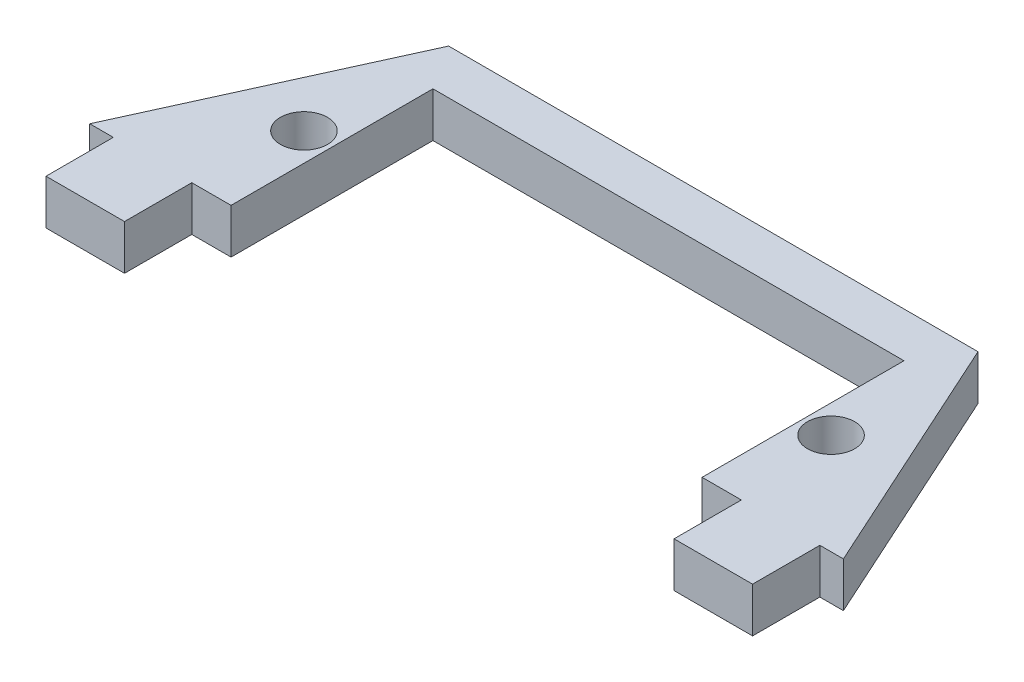
SolidWorks part; units mm, degrees
ref_plane "Front" through (0, 0, 0) normal (0, 0, 1) x (1, 0, 0)
ref_plane "Top" through (0, 0, 0) normal (0, 1, 0) x (1, 0, 0)
ref_plane "Right" through (0, 0, 0) normal (1, 0, 0) x (0, 0, -1)
sketch "Croquis1" plane through (0, 0, 0) normal (0, 1, 0) x (1, 0, 0)
  line L0 (-319.2972, 0) -> (15645.5623, 0) construction
  line L1 (0, -319.2972) -> (0, 15645.5623) construction
  line L2 (-10.5, 0) -> (-10.5, 9)
  line L3 (-10.5, 9) -> (10.5, 9)
  line L4 (10.5, 9) -> (10.5, 0)
  line L5 (-11.8, 11) -> (-16.8, 0)
  line L6 (-11.8, 11) -> (11.8, 11)
  line L7 (11.8, 11) -> (16.8, 0)
  line L9 (-16.8, 0) -> (-15.75, 0)
  line L10 (-15.75, 0) -> (-15.75, -3)
  line L11 (-15.75, -3) -> (-12.25, -3)
  line L12 (-12.25, -3) -> (-12.25, 0)
  line L13 (-12.25, 0) -> (-10.5, 0)
  line L15 (12.25, 0) -> (10.5, 0)
  line L16 (12.25, -3) -> (12.25, 0)
  line L17 (15.75, -3) -> (12.25, -3)
  line L18 (15.75, 0) -> (15.75, -3)
  line L19 (16.8, 0) -> (15.75, 0)
  line L23 (6, -319.2972) -> (6, 15645.5623) construction
  line L24 (-6, -319.2972) -> (-6, 15645.5623) construction
  circle A0 centre (-11.75, 4.5) radius 1.05
  circle A1 centre (11.75, 4.5) radius 1.05
  point P46 (16.8, 11)
  dimension "D5" = 2.1
  dimension "D6" = 1.25
  dimension "D10" = 11
  dimension "D14" = 4.5
  dimension "D1" = 9
  dimension "D2" = 21
  dimension "D3" = 3
  dimension "D7" = 3.5
  dimension "D8" = 1.05
  dimension "D13" = 31.5
extrude "Saliente-Extruir1" add sketch "Croquis1" along normal blind 2
